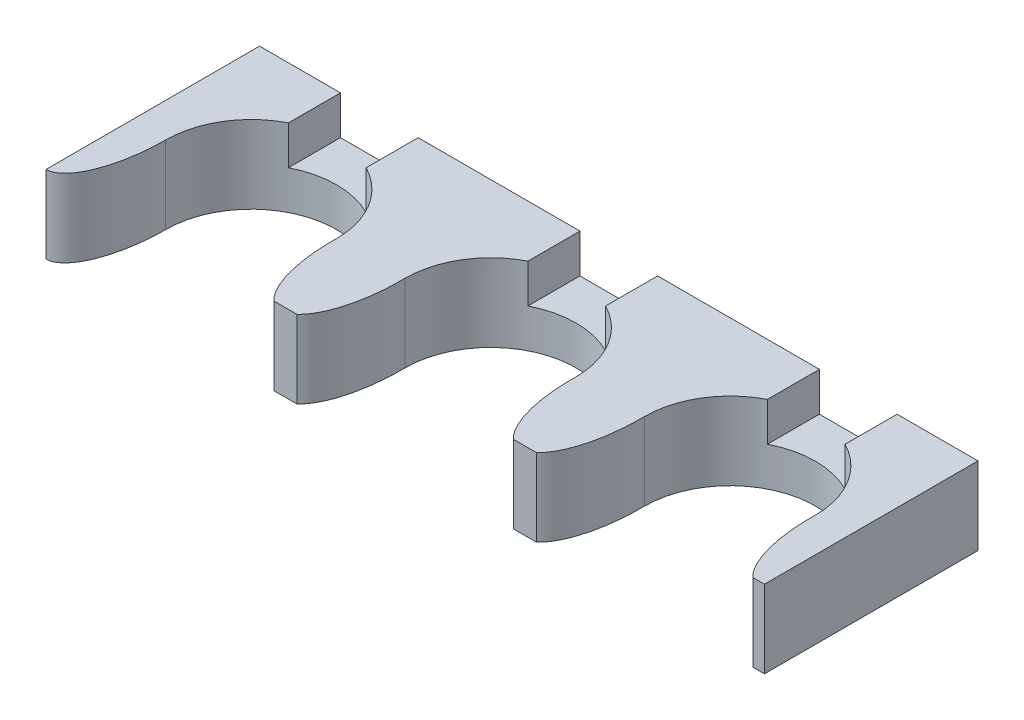
SolidWorks part; units mm, degrees
ref_plane "Front Plane" through (0, 0, 0) normal (0, 0, 1) x (1, 0, 0)
ref_plane "Top Plane" through (0, 0, 0) normal (0, 1, 0) x (1, 0, 0)
ref_plane "Right Plane" through (0, 0, 0) normal (1, 0, 0) x (0, 0, -1)
sketch "Sketch1" plane through (0, 0, 0) normal (0, 1, 0) x (1, 0, 0)
  line L1 (-79.0983, 46.8881) -> (390.8017, 46.8881)
  line L2 (-79.0983, 46.8881) -> (-79.0983, -92.8119)
  line L3 (-79.0983, -92.8119) -> (390.8017, -92.8119)
  line L4 (390.8017, 46.8881) -> (390.8017, -92.8119)
  dimension "D1" = 469.9
  dimension "D2" = 139.7
extrude "Boss-Extrude1" add sketch "Sketch1" along normal blind 50.8
sketch "Sketch2" plane through (0, 50.8, 0) normal (0, 1, 0) x (1, 0, 0)
  line L0 (-79.0983, -92.8119) -> (390.8017, -92.8119) construction
  line L1 (-79.0983, 46.8881) -> (-79.0983, -92.8119) construction
  line L2 (-56.6618, -36.9319) -> (-56.6618, -92.8119)
  line L3 (55.0982, -36.9319) -> (55.0982, -92.8119)
  line L4 (99.9717, -36.9319) -> (99.9717, -92.8119)
  line L5 (211.7317, -36.9319) -> (211.7317, -92.8119)
  line L6 (256.6051, -36.9319) -> (256.6051, -92.8119)
  line L7 (368.3651, -36.9319) -> (368.3651, -92.8119)
  line L8 (390.8017, -92.8119) -> (390.8017, 46.8881) construction
  line L9 (390.8017, 46.8881) -> (-79.0983, 46.8881) construction
  circle A0 centre (155.8517, -36.9319) radius 55.88
  circle A1 centre (312.4851, -36.9319) radius 55.88
  circle A2 centre (-0.7818, -36.9319) radius 55.88
  line M2 (-79.0983, -92.8119) -> (390.8017, -92.8119)
  dimension "D1" = 111.76
  dimension "D2" = 234.95
  dimension "D8" = 83.82
  dimension "D7" = 156.6334
  dimension "D5" = 78.3166
  dimension "D6" = 78.3166
  dimension "D9" = 83.82
  dimension "D3" = 2
  dimension "D4" = 2
extrude "Cut-Extrude3" cut sketch "Sketch2" against normal through all contours A2 L3 M2 | A2 L2 M2 | A0 L4 M2 | A0 L5 M2 | A1 L6 M2 | A1 L7 M2 | A1 | A0 | A2
sketch "Sketch3" plane through (0, 50.8, 0) normal (0, 1, 0) x (1, 0, 0)
  line L0 (-0.7818, -36.9319) -> (390.8017, -36.9319)
  line L1 (390.8017, -92.8119) -> (390.8017, 46.8881) construction
  line L2 (-0.7818, -36.9319) -> (-79.0983, -36.9319)
  line L3 (-79.0983, 46.8881) -> (-79.0983, -92.8119) construction
  ellipse E0 centre (-79.0983, -36.9319) end of major axis (-79.0983, -92.8119) minor radius 22.4366
  ellipse E1 centre (77.5181, -40.1069) end of major axis (77.5181, -95.9869) minor radius 22.4366
  ellipse E2 centre (234.1345, -40.1069) end of major axis (234.1345, -95.9869) minor radius 22.4366
  ellipse E3 centre (390.7509, -40.1069) end of major axis (390.7509, -95.9869) minor radius 22.4366
  line M2 (55.0982, -36.9319) -> (55.0982, -92.8119)
  line M3 (55.0982, -92.8119) -> (99.9717, -92.8119)
  line M4 (99.9717, -92.8119) -> (99.9717, -36.9319)
  line M6 (211.7317, -36.9319) -> (211.7317, -92.8119)
  line M7 (211.7317, -92.8119) -> (256.6051, -92.8119)
  line M8 (256.6051, -92.8119) -> (256.6051, -36.9319)
  line M10 (368.3651, -36.9319) -> (368.3651, -92.8119)
  line M11 (368.3651, -92.8119) -> (390.8017, -92.8119)
  line M15 (-79.0983, -92.8119) -> (-56.6618, -92.8119)
  line M16 (-56.6618, -92.8119) -> (-56.6618, -36.9319)
extrude "Cut-Extrude5" cut sketch "Sketch3" against normal through all contours E0 M15 M16 | E1 M2 M3 | E1 L0 M3 M4 | E2 M6 M7 | E2 L0 M7 M8 | E3 M10 M11
sketch "Sketch5" plane through (0, 0, -46.8881) normal (0, 0, -1) x (-1, 0, 0)
  line L0 (-390.8017, 50.8) -> (79.0983, 50.8) construction
  line L1 (-337.8858, 50.8) -> (-287.0858, 50.8)
  line L2 (-337.8858, 50.8) -> (-337.8858, 25.4)
  line L3 (-337.8858, 25.4) -> (-287.0858, 25.4)
  line L4 (-287.0858, 50.8) -> (-287.0858, 25.4)
  line L5 (-390.8017, 50.8) -> (-390.8017, 0) construction
  line L6 (79.0983, 50.8) -> (79.0983, 0) construction
  line L7 (-181.2517, 50.8) -> (-130.4517, 50.8)
  line L8 (-181.2517, 50.8) -> (-181.2517, 25.4)
  line L9 (-181.2517, 25.4) -> (-130.4517, 25.4)
  line L10 (-130.4517, 50.8) -> (-130.4517, 25.4)
  line L11 (-24.6175, 50.8) -> (26.1825, 50.8)
  line L12 (-24.6175, 50.8) -> (-24.6175, 25.4)
  line L13 (-24.6175, 25.4) -> (26.1825, 25.4)
  line L14 (26.1825, 50.8) -> (26.1825, 25.4)
  dimension "D1" = 50.8
  dimension "D2" = 25.4
  dimension "D3" = 52.9158
  dimension "D4" = 50.8
  dimension "D5" = 50.8
  dimension "D6" = 25.4
  dimension "D7" = 25.4
  dimension "D8" = 52.9158
  dimension "D9" = 209.55
  dimension "D10" = 209.55
extrude "Cut-Extrude6" cut sketch "Sketch5" against normal through all
